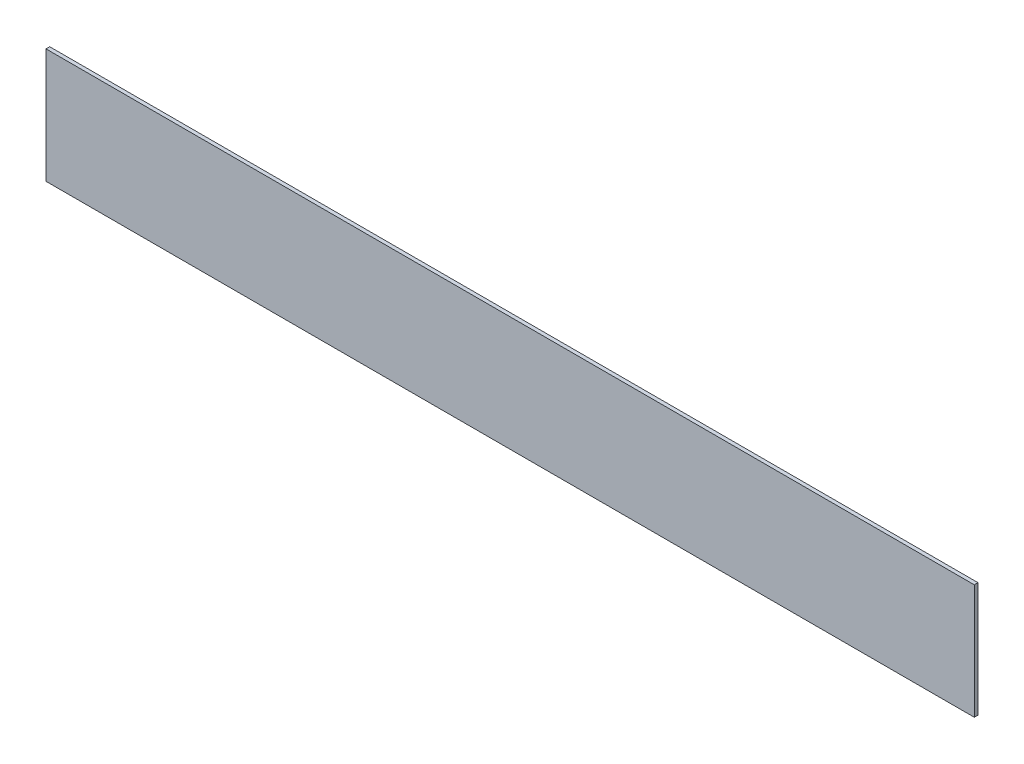
SolidWorks part; units mm, degrees
ref_plane "Front Plane" through (0, 0, 0) normal (0, 0, 1) x (1, 0, 0)
ref_plane "Top Plane" through (0, 0, 0) normal (0, 1, 0) x (1, 0, 0)
ref_plane "Right Plane" through (0, 0, 0) normal (1, 0, 0) x (0, 0, -1)
sketch "Sketch1" plane through (0, 0, 0) normal (0, 0, 1) x (1, 0, 0)
  line L0 (2500, 309) -> (2500, 0)
  line L1 (2500, 309) -> (0, 309)
  line L2 (2500, 0) -> (0, 0)
  line L3 (0, 309) -> (0, 0)
other "Pen Sketch1" parameters "D1"=69.7562, "D2"=44.2015
extrude "Boss-Extrude1" add sketch "Sketch1" along normal blind 10
